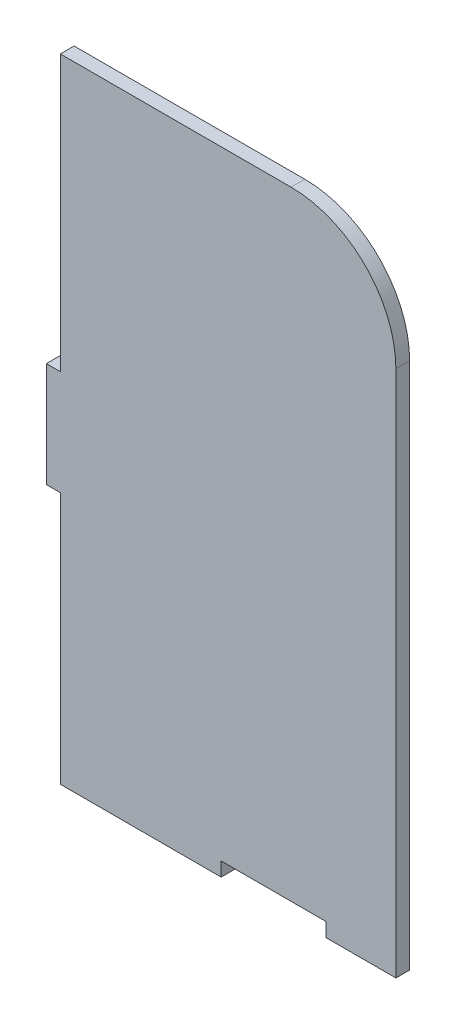
SolidWorks part; units mm, degrees
ref_plane "Front Plane" through (0, 0, 0) normal (0, 0, 1) x (1, 0, 0)
ref_plane "Top Plane" through (0, 0, 0) normal (0, 1, 0) x (1, 0, 0)
ref_plane "Right Plane" through (0, 0, 0) normal (1, 0, 0) x (0, 0, -1)
sketch "Sketch1" plane through (0, 0, 0) normal (0, 0, 1) x (1, 0, 0)
  line L0 (215.8296, -10.16) -> (383.5218, -10.16)
  line L1 (459.7218, -86.36) -> (459.7218, -469.9)
  line L2 (215.8296, -10.16) -> (215.8296, -210.16)
  line L4 (215.8296, -172.7939) -> (215.8296, -91.4769) construction
  line L6 (215.8296, -210.16) -> (205.6631, -210.16)
  line L7 (205.6631, -172.7939) -> (205.6631, -91.4769) construction
  line L8 (205.6631, -210.16) -> (205.6631, -286.36)
  line L9 (205.6631, -172.7939) -> (205.6631, -254.1108) construction
  line L10 (205.6631, -286.36) -> (215.8296, -286.36)
  line L11 (215.8296, -254.1108) -> (215.8296, -172.7939) construction
  line L12 (215.8296, -286.36) -> (215.8296, -469.9)
  line L13 (215.8296, -469.9) -> (332.7218, -469.9)
  line L14 (408.9218, -469.9) -> (408.9218, -459.74)
  line L15 (408.9218, -459.74) -> (332.7218, -459.74)
  line L16 (332.7218, -459.74) -> (332.7218, -469.9)
  line L17 (408.9218, -469.9) -> (459.7218, -469.9)
  arc A2 (459.7218, -86.36) -> (383.5218, -10.16) centre (383.5218, -86.36) ccw
  dimension "D1" = 76.2
  dimension "D2" = 200
extrude "Boss-Extrude1" add sketch "Sketch1" against normal blind 10
